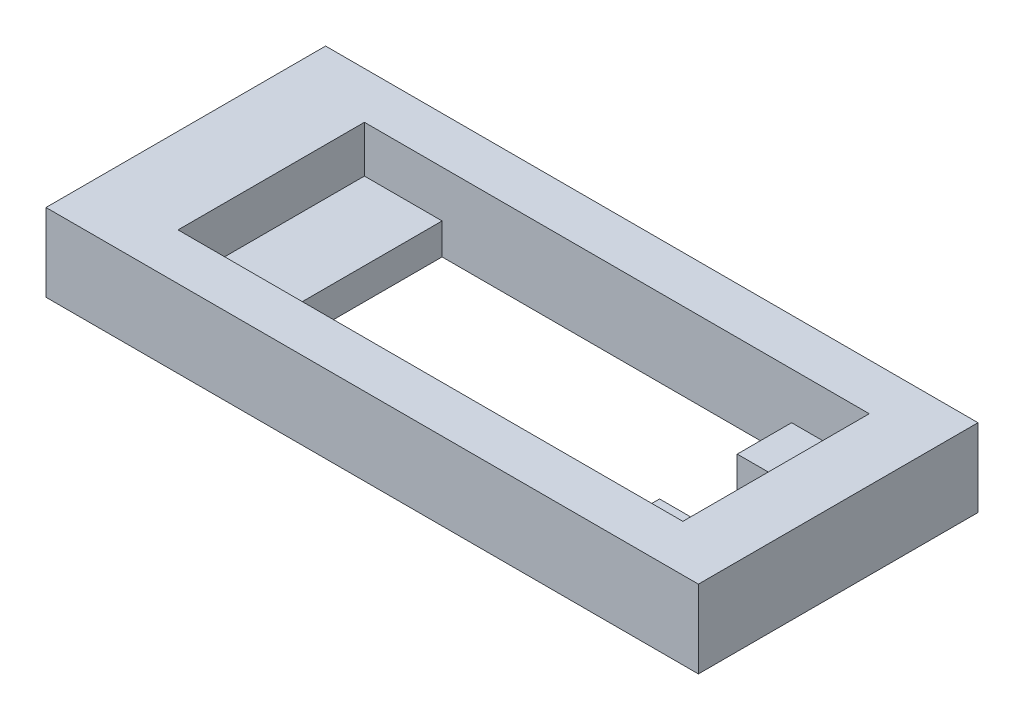
SolidWorks part; units mm, degrees
ref_plane "Front Plane" through (0, 0, 0) normal (0, 0, 1) x (1, 0, 0)
ref_plane "Top Plane" through (0, 0, 0) normal (0, 1, 0) x (1, 0, 0)
ref_plane "Right Plane" through (0, 0, 0) normal (1, 0, 0) x (0, 0, -1)
sketch "Sketch1" plane through (0, 0, 0) normal (0, 0, 1) x (1, 0, 0)
  line L3 (21, -5.0081) -> (21, 0)
  line L4 (21, 0) -> (-21, 0)
  line L5 (-21, 0) -> (-21, -5.0081)
  line L8 (-21, -5.0081) -> (21, -5.0081)
  point P0 (0, 0)
  dimension "D1" = 42
extrude "Boss-Extrude1" add sketch "Sketch1" along normal blind 18
sketch "Sketch2" plane through (0, 0, 0) normal (0, 1, 0) x (1, 0, 0)
  line L0 (21, -18) -> (21, 0) construction
  line L1 (17, -3) -> (-15.5, -3)
  line L2 (17, -3) -> (17, -15)
  line L3 (17, -15) -> (-15.5, -15)
  line L4 (-15.5, -3) -> (-15.5, -15)
  line L5 (17, -3) -> (-15.5, -15) construction
  line L6 (17, -15) -> (-15.5, -3) construction
  line L7 (21, 0) -> (-21, 0) construction
  circle A0 centre (6.3, -9) radius 2.325 construction
  point P0 (0.75, -9)
  dimension "D5" = 4.65
  dimension "D6" = 4
  dimension "D1" = 32.5
  dimension "D2" = 12
  dimension "D3" = 10.7
  dimension "D4" = 3
extrude "Cut-Extrude1" cut sketch "Sketch2" against normal blind 3
sketch "Sketch3" plane through (0, -3, 0) normal (0, 1, 0) x (1, 0, 0)
  line L0 (-15.5, -15) -> (17, -15) construction
  line L1 (-10.5, -3) -> (12, -3)
  line L2 (-10.5, -3) -> (-10.5, -15)
  line L3 (-10.5, -15) -> (12, -15)
  line L4 (12, -3) -> (12, -15)
  line L5 (-10.5, -3) -> (12, -15) construction
  line L6 (-10.5, -15) -> (12, -3) construction
  line L7 (17, -3) -> (-15.5, -3) construction
  line L9 (17, -15) -> (17, -3) construction
  line L10 (-15.5, -3) -> (-15.5, -15) construction
  point P0 (0.75, -9)
  dimension "D1" = 5
  dimension "D2" = 5
extrude "Cut-Extrude2" cut sketch "Sketch3" against normal up to next
sketch "Sketch4" plane through (0, -3, 0) normal (0, 1, 0) x (1, 0, 0)
  line L0 (12, -15) -> (12, -3) construction
  line L1 (17, -6.5) -> (12, -6.5)
  line L2 (17, -6.5) -> (17, -11.5)
  line L3 (17, -11.5) -> (12, -11.5)
  line L4 (12, -6.5) -> (12, -11.5)
  line L5 (17, -6.5) -> (12, -11.5) construction
  line L6 (17, -11.5) -> (12, -6.5) construction
  point P0 (14.5, -9)
  point P9 (12, -9)
  dimension "D1" = 5
  dimension "D2" = 5
extrude "Cut-Extrude3" cut sketch "Sketch4" against normal up to next
